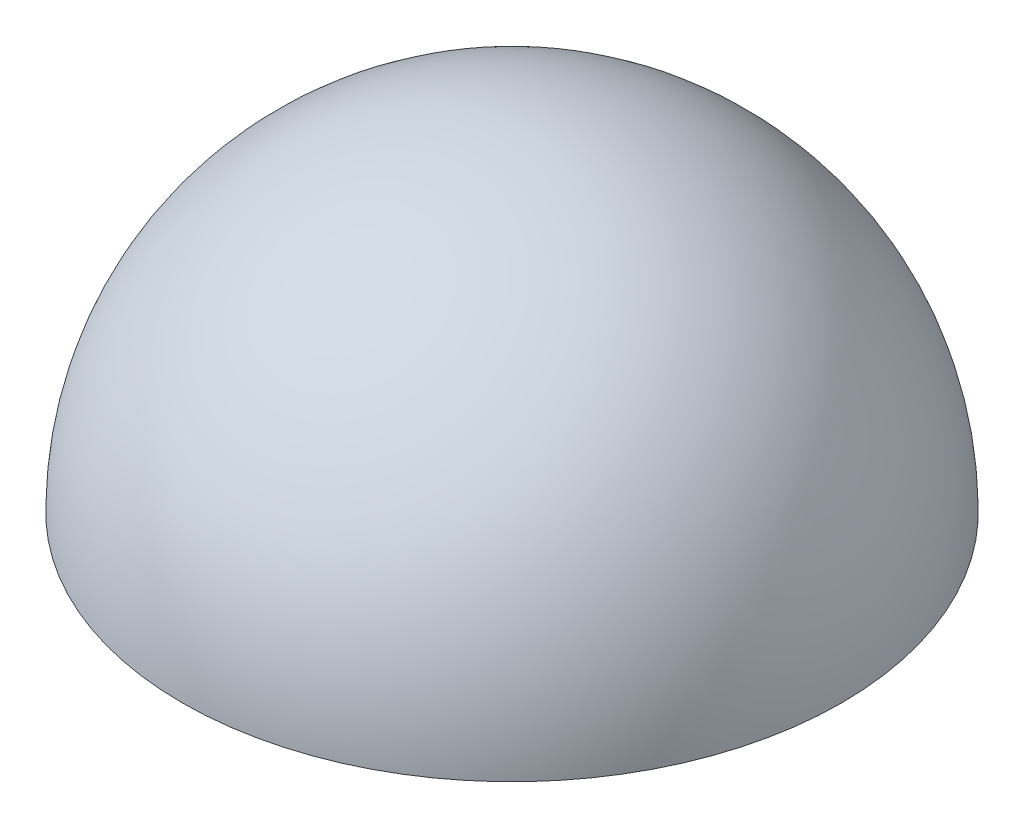
SolidWorks part; units mm, degrees
material "Glass"
ref_plane "Front Plane" through (0, 0, 0) normal (0, 0, 1) x (1, 0, 0)
ref_plane "Top Plane" through (0, 0, 0) normal (0, 1, 0) x (1, 0, 0)
ref_plane "Right Plane" through (0, 0, 0) normal (1, 0, 0) x (0, 0, -1)
sketch "Sketch1" plane through (0, 0, 0) normal (0, 0, 1) x (1, 0, 0)
  line L0 (0, 29.4625) -> (0, -34.1782) construction
  line L1 (-41.5825, 0) -> (63.5599, 0) construction
  line L2 (0, 25) -> (0, 23)
  line L3 (23, 0) -> (25, 0)
  arc A0 (23, 0) -> (0, 23) centre (0, 0) ccw
  arc A1 (25, 0) -> (0, 25) centre (0, 0) ccw
  dimension "D1" = 25
  dimension "D2" = 2
revolve "Revolve1" add sketch "Sketch1" angle 360 about L0
